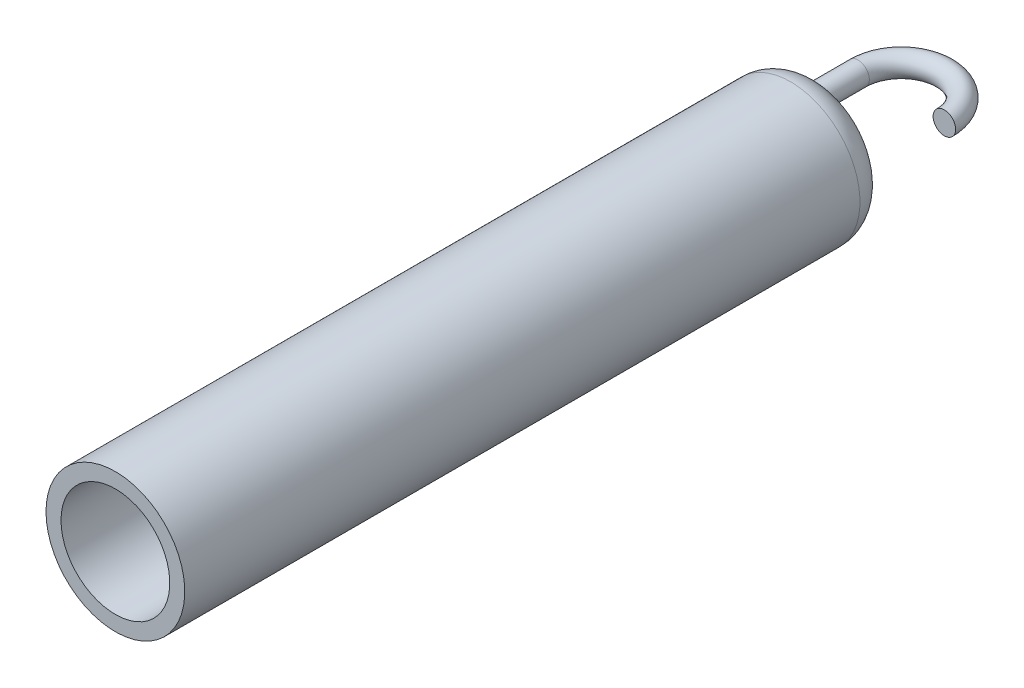
SolidWorks part; units mm, degrees
ref_plane "Plan de face" through (0, 0, 0) normal (0, 0, 1) x (1, 0, 0)
ref_plane "Plan de dessus" through (0, 0, 0) normal (0, 1, 0) x (1, 0, 0)
ref_plane "Plan de droite" through (0, 0, 0) normal (1, 0, 0) x (0, 0, -1)
sketch "Esquisse2" plane through (0, 0, 0) normal (0, 0, 1) x (1, 0, 0)
  circle A0 centre (0, 0) radius 7.25
  circle A1 centre (0, 0) radius 9.25
  dimension "D1" = 18.5
  dimension "D2" = 2
  dimension "D3" = 14.5
extrude "Boss.-Extru.1" add sketch "Esquisse2" along normal mid plane 90
sketch "Esquisse3" plane through (0, 0, 0) normal (0, 1, 0) x (1, 0, 0)
  line L0 (-5.25, 49) -> (0, 49)
  line L1 (-9.25, 45) -> (-9.25, -45) construction
  line L2 (0, 49) -> (0, 45)
  line L3 (7.25, 45) -> (-7.25, 45) construction
  line L4 (0, 45) -> (-9.25, 45)
  arc A0 (-9.25, 45) -> (-5.25, 49) centre (-5.25, 45) cw
  point P3 (-7.3575, 48.2925)
  dimension "D1" = 4
revolve "Révolution1" add sketch "Esquisse3" angle 360 about L2
sketch "Esquisse4" plane through (0, 0, -45) normal (0, 0, 1) x (1, 0, 0)
  line L0 (0, -10.175) -> (0, 10.175) construction
  circle A0 centre (-5.75, 0) radius 1.5
  circle A2 centre (0, 0) radius 7.25 construction
  circle A3 centre (0, 0) radius 7.25 construction
  circle A4 centre (5.75, 0) radius 1.5
  point P4 (-8.6442, -0.3175)
  point P10 (-7.25, 0)
  dimension "D1" = 3
sketch "Esquisse5" plane through (0, 0, 0) normal (1, 0, 0) x (0, 0, -1)
  line L0 (49, -5.25) -> (49, 5.25) construction
  circle A0 centre (65.5, 0) radius 1.5
  point P2 (56.8627, 0)
  dimension "D1" = 3
  dimension "D2" = 16.5
sketch "Esquisse6" plane through (0, 0, 0) normal (0, 1, 0) x (1, 0, 0)
  line L0 (-4.25, 45) -> (-4.25, 59.75)
  line L1 (0, -10.175) -> (0, 10.175) construction
  line L5 (0, 64) -> (0, 67) construction
  arc A0 (-4.25, 59.75) -> (4.25, 59.75) centre (0, 59.75) cw
  point P4 (0, 64)
  point P5 (2.65, 44.6296)
  point P6 (0, 0)
  point P7 (3.4149, 59.3922)
  point P8 (-4.25, 45)
  point P9 (0, 0)
  point P10 (0, 0)
  point P11 (0, 0)
  point P15 (4.25, 45)
  point P16 (0, 0)
sweep "Balayage3" add profiles "Esquisse5" path "Esquisse6"
